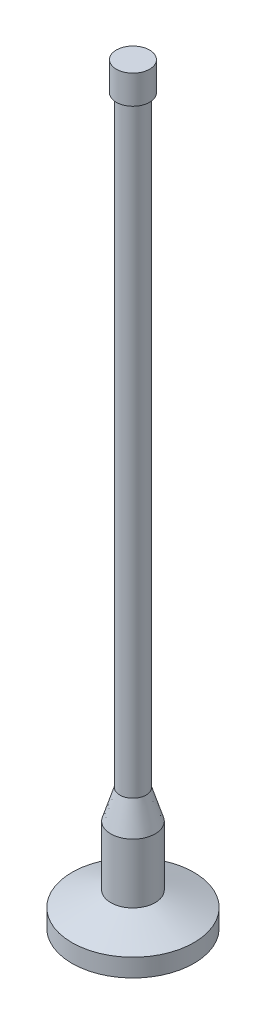
SolidWorks part; units mm, degrees
ref_plane "Front Plane" through (0, 0, 0) normal (0, 0, 1) x (1, 0, 0)
ref_plane "Top Plane" through (0, 0, 0) normal (0, 1, 0) x (1, 0, 0)
ref_plane "Right Plane" through (0, 0, 0) normal (1, 0, 0) x (0, 0, -1)
sketch "Sketch1" plane through (0, 0, 0) normal (0, 0, 1) x (1, 0, 0)
  line L0 (0, 0) -> (44, 0)
  line L1 (44, 0) -> (44, 13)
  line L2 (44, 13) -> (16, 24)
  line L3 (16, 24) -> (16, 67)
  line L4 (16, 67) -> (9.5, 88)
  line L5 (9.5, 88) -> (9.5, 522.2875)
  line L6 (9.5, 522.2875) -> (12, 522.2875)
  line L7 (12, 522.2875) -> (12, 543)
  line L8 (12, 543) -> (0, 543)
  line L9 (0, 289.3963) -> (0, 0) construction
  line L10 (0, 0) -> (0, 543)
  dimension "D1" = 44
  dimension "D2" = 13
  dimension "D3" = 24
  dimension "D4" = 88
  dimension "D5" = 67
  dimension "D6" = 543
  dimension "D7" = 522.2875
  dimension "D8" = 12
  dimension "D9" = 9.5
  dimension "D10" = 16
revolve "Revolve1" add sketch "Sketch1" angle 360 about L9
